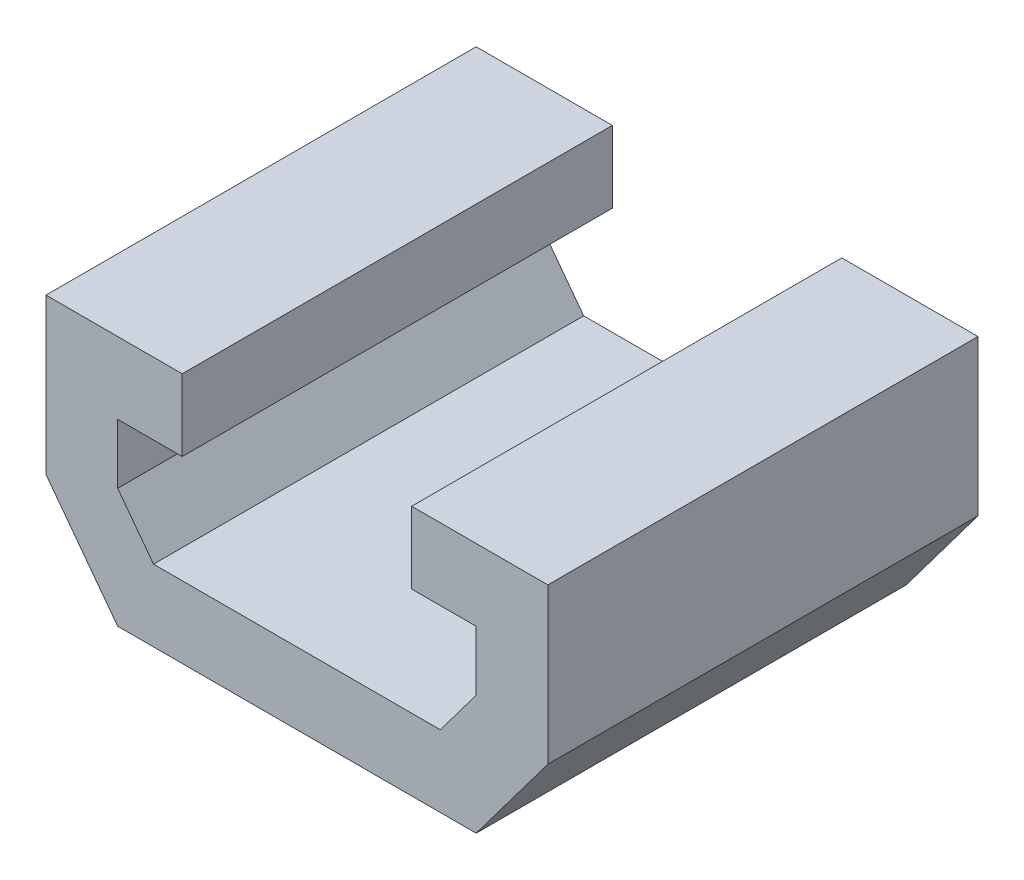
SolidWorks part; units mm, degrees
ref_plane "Front Plane" through (0, 0, 0) normal (0, 0, 1) x (1, 0, 0)
ref_plane "Top Plane" through (0, 0, 0) normal (0, 1, 0) x (1, 0, 0)
ref_plane "Right Plane" through (0, 0, 0) normal (1, 0, 0) x (0, 0, -1)
sketch "Sketch1" plane through (0, 0, 0) normal (0, 0, 1) x (1, 0, 0)
  line L0 (0, 0) -> (-2.54, 0)
  line L5 (-2.54, 0) -> (-3.175, 0.8467)
  line L6 (-3.175, 0.8467) -> (-3.175, 1.905)
  line L7 (-3.175, 1.905) -> (-2.032, 1.905)
  point P2 (-3.81, 0.9631)
  dimension "D1" = 1.905
  dimension "D2" = 3.175
  dimension "D3" = 2.54
  dimension "D4" = 2.032
extrude "Extrude-Thin1" add sketch "Sketch1" along normal blind 7.62 thin thin type one direction reverse wall 1.27
mirror "Mirror1" about plane through (0, 0, 7.62) normal (1, 0, 0) of bodies 102
